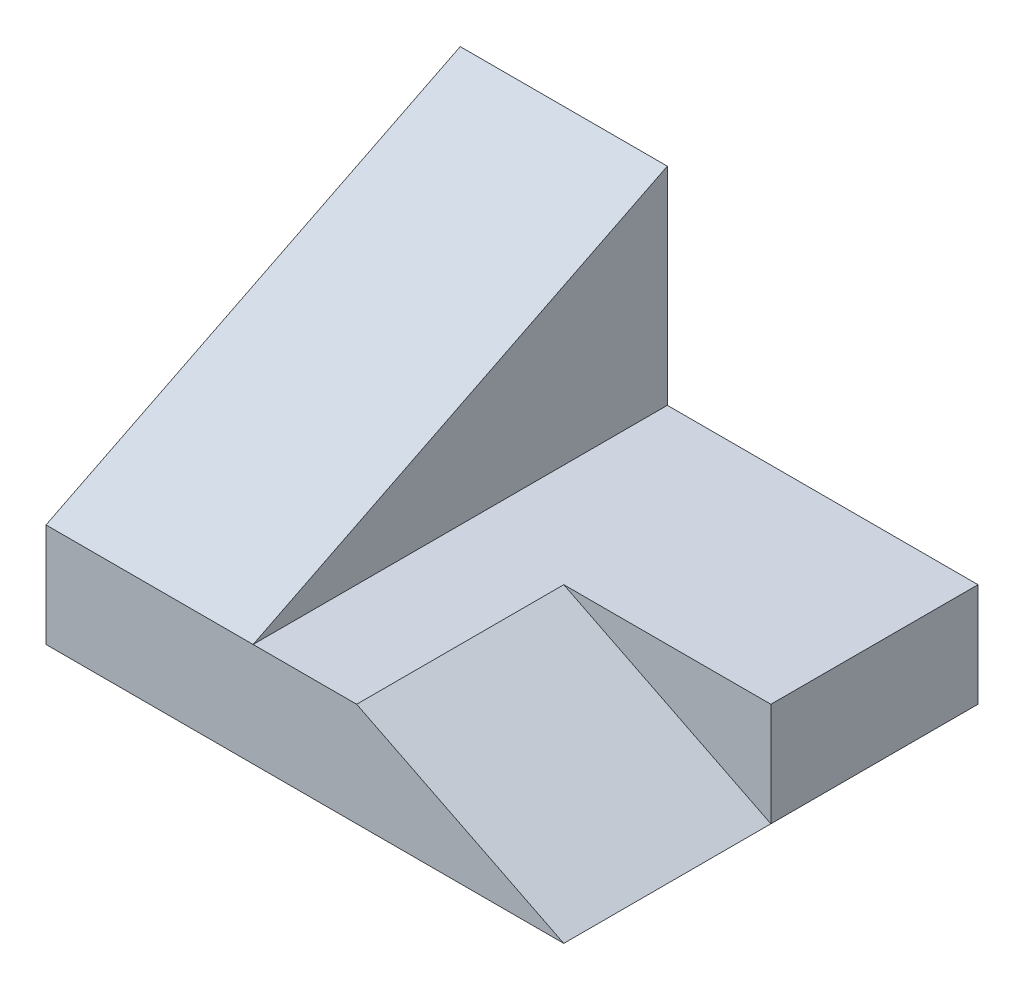
SolidWorks part; units mm, degrees
ref_plane "Front Plane" through (0, 0, 0) normal (0, 0, 1) x (1, 0, 0)
ref_plane "Top Plane" through (0, 0, 0) normal (0, 1, 0) x (1, 0, 0)
ref_plane "Right Plane" through (0, 0, 0) normal (1, 0, 0) x (0, 0, -1)
sketch "Sketch2" plane through (0, 0, 0) normal (0, 1, 0) x (1, 0, 0)
  line L1 (0, 0) -> (127, 0)
  line L2 (0, 0) -> (0, 101.6)
  line L3 (0, 101.6) -> (127, 101.6)
  line L4 (127, 0) -> (127, 101.6)
  dimension "D1" = 101.6
  dimension "D2" = 127
extrude "Boss-Extrude1" add sketch "Sketch2" along normal blind 25.4
sketch "Sketch4" plane through (0, 0, 0) normal (0, 0, 1) x (1, 0, 0)
  line L0 (0, 25.4) -> (127, 25.4) construction
  line L1 (127, 25.4) -> (127, 0) construction
  line L2 (76.2, 25.4) -> (127, 25.4)
  line L3 (127, 25.4) -> (127, 0)
  line L4 (76.2, 25.4) -> (127, 0)
  dimension "D1" = 50.8
extrude "Cut-Extrude2" cut sketch "Sketch4" against normal blind 50.8
ref_plane "Plane1" through (0, 0, 0) normal (-1, 0, 0) x (0, 0, 1)
sketch "Sketch5" plane through (0, 0, 0) normal (-1, 0, 0) x (0, 0, 1)
  line L0 (-101.6, 25.4) -> (0, 25.4) construction
  line L1 (-101.6, 25.4) -> (0, 25.4)
  line L2 (-101.6, 25.4) -> (-101.6, 76.2)
  line L3 (-101.6, 76.2) -> (0, 25.4)
  dimension "D1" = 50.8
extrude "Boss-Extrude2" add sketch "Sketch5" against normal blind 50.8
